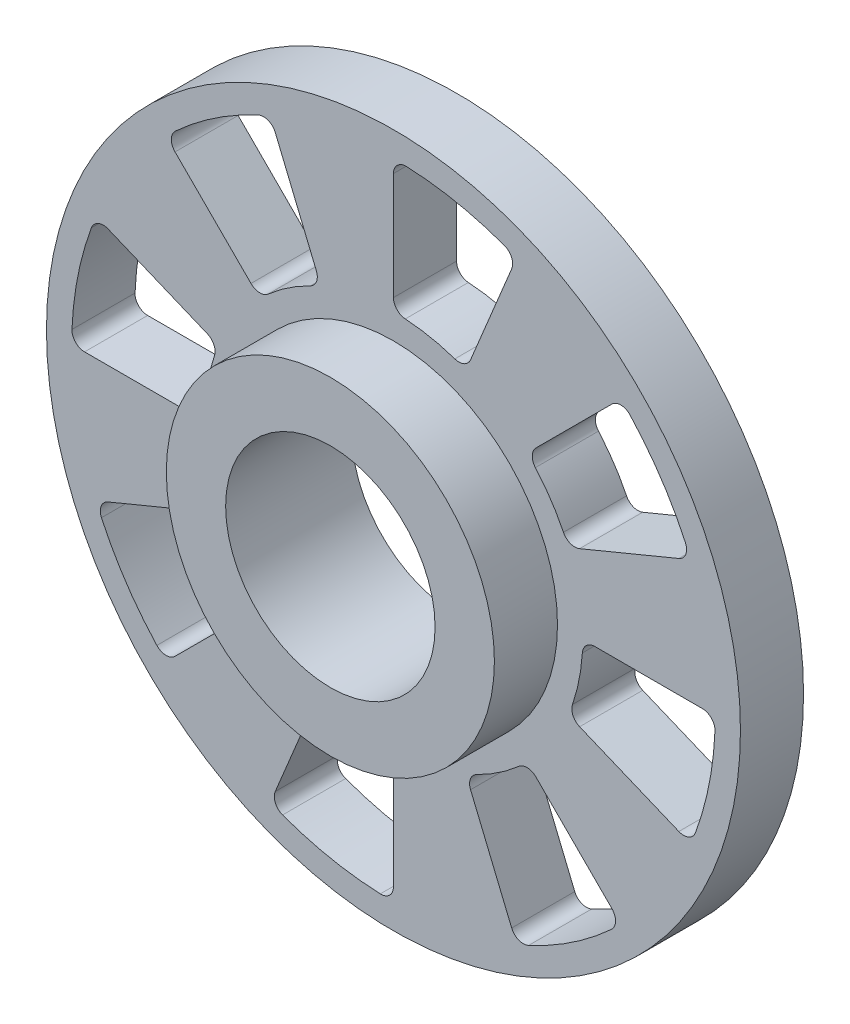
SolidWorks part; units mm, degrees
ref_plane "Front Plane" through (0, 0, 0) normal (0, 0, 1) x (1, 0, 0)
ref_plane "Top Plane" through (0, 0, 0) normal (0, 1, 0) x (1, 0, 0)
ref_plane "Right Plane" through (0, 0, 0) normal (1, 0, 0) x (0, 0, -1)
sketch "Sketch1" plane through (0, 0, 0) normal (0, 0, 1) x (1, 0, 0)
  circle A0 centre (0, 0) radius 4.15
  circle A1 centre (0, 0) radius 13.75
  dimension "D1" = 27.5
  dimension "D2" = 8.3
extrude "Boss-Extrude1" add sketch "Sketch1" along normal blind 2.5
sketch "Sketch2" plane through (0, 0, 2.5) normal (0, 0, 1) x (1, 0, 0)
  circle A0 centre (0, 0) radius 4.15
  circle A1 centre (0, 0) radius 6.5
  circle A2 centre (0, 0) radius 4.15 construction
  circle A3 centre (0, 0) radius 4 construction
  dimension "D1" = 8
  dimension "D2" = 2.5
extrude "Boss-Extrude2" add sketch "Sketch2" along normal blind 2.5
sketch "Sketch5" plane through (0, 0, 0) normal (0, 0, 1) x (1, 0, 0)
  line L0 (0, 0) -> (0, 7.5) construction
  line L1 (0, 7.5) -> (0, 12.75)
  line L2 (0, 0) -> (2.8701, 6.9291) construction
  line L3 (2.8701, 6.9291) -> (4.8792, 11.7795)
  circle A0 centre (0, 0) radius 12.75
  circle A1 centre (0, 0) radius 7.5
  circle A2 centre (0, 0) radius 13.75 construction
  circle A3 centre (0, 0) radius 6.5 construction
  dimension "D1" = 1
  dimension "D2" = 1
  dimension "D3" = 22.5
extrude "Cut-Extrude1" cut sketch "Sketch5" along normal through all contours A1 L3 A0 L1
fillet "Fillet1" radius 0.5 4 edges at (2.8701, 6.9291, 1.25) (4.8792, 11.7795, 1.25) (0, 7.5, 1.25) (0, 12.75, 1.25)
pattern_circular "CirPattern1" count 8 over 360 about axis through (0, 0, 0) along (0, 0, 1) of "Cut-Extrude1", "Fillet1"
